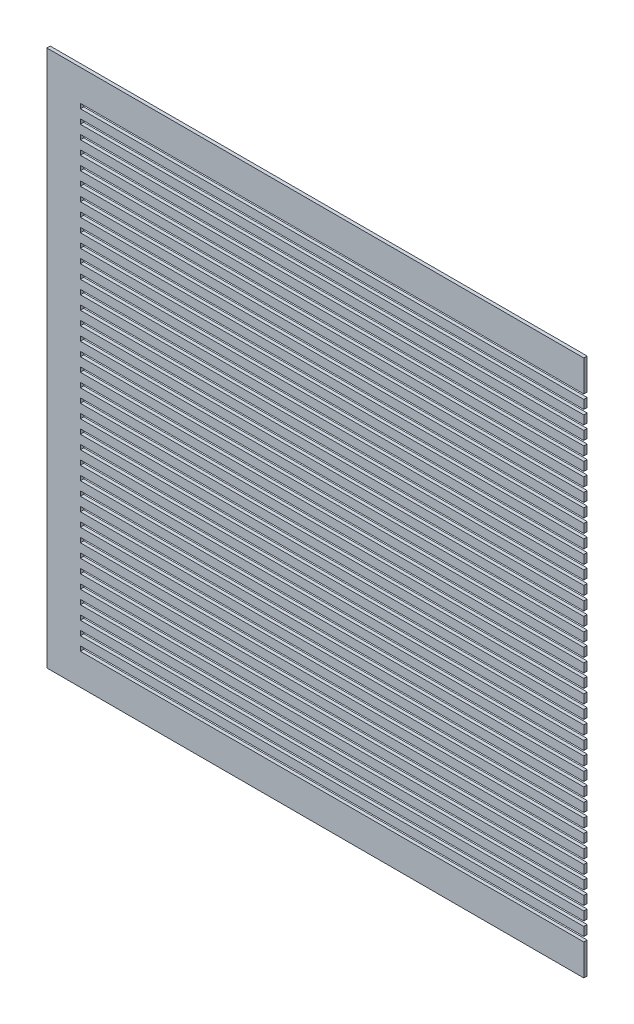
SolidWorks part; units mm, degrees
ref_plane "前视基准面" through (0, 0, 0) normal (0, 0, 1) x (1, 0, 0)
ref_plane "上视基准面" through (0, 0, 0) normal (0, 1, 0) x (1, 0, 0)
ref_plane "右视基准面" through (0, 0, 0) normal (1, 0, 0) x (0, 0, -1)
sketch "草图1" plane through (0, 0, 0) normal (0, 0, 1) x (1, 0, 0)
  line L5 (-75, -66.4634) -> (-75, -65.0634)
  line L6 (-75, -65.0634) -> (75, -65.0634)
  line L7 (-75, -66.4634) -> (75, -66.4634)
  line L8 (-75, -65.0634) -> (75, -65.0634)
  line L9 (-75, -65.7634) -> (75, -65.7634) construction
  line L10 (-75, -62.4634) -> (-75, -61.0634)
  line L11 (-75, -61.0634) -> (75, -61.0634)
  line L13 (-75, -62.4634) -> (75, -62.4634)
  line L14 (-75, -61.0634) -> (75, -61.0634)
  line L15 (-75, -61.7634) -> (75, -61.7634) construction
  line L17 (-75, -58.4634) -> (-75, -57.0634)
  line L18 (75, -70.4634) -> (75, -79.7634)
  line L20 (-75, -57.0634) -> (75, -57.0634)
  line L21 (-75, -58.4634) -> (75, -58.4634)
  line L22 (75, 80.2366) -> (-85, 80.2366)
  line L23 (-85, 80.2366) -> (-85, -79.7634)
  line L25 (-75, -57.0634) -> (75, -57.0634)
  line L26 (-75, -57.7634) -> (75, -57.7634) construction
  line L28 (-75, -54.4634) -> (-75, -53.0634)
  line L29 (-75, -53.0634) -> (75, -53.0634)
  line L30 (-85, -79.7634) -> (75, -79.7634)
  line L31 (-75, -54.4634) -> (75, -54.4634)
  line L33 (-75, -53.0634) -> (75, -53.0634)
  line L34 (-75, -53.7634) -> (75, -53.7634) construction
  line L36 (-75, -50.4634) -> (-75, -49.0634)
  line L37 (-75, -49.0634) -> (75, -49.0634)
  line L38 (-75, -50.4634) -> (75, -50.4634)
  line L39 (-75, -49.0634) -> (75, -49.0634)
  line L41 (-75, -49.7634) -> (75, -49.7634) construction
  line L42 (-75, -46.4634) -> (-75, -45.0634)
  line L44 (-75, -45.0634) -> (75, -45.0634)
  line L45 (-75, -46.4634) -> (75, -46.4634)
  line L46 (-75, -45.0634) -> (75, -45.0634)
  line L47 (-75, -45.7634) -> (75, -45.7634) construction
  line L49 (-75, -42.4634) -> (-75, -41.0634)
  line L50 (-75, -41.0634) -> (75, -41.0634)
  line L52 (-75, -42.4634) -> (75, -42.4634)
  line L53 (-75, -41.0634) -> (75, -41.0634)
  line L54 (-75, -70.4634) -> (-75, -69.0634)
  line L55 (-75, -41.7634) -> (75, -41.7634) construction
  line L57 (-75, -38.4634) -> (-75, -37.0634)
  line L58 (-75, -37.0634) -> (75, -37.0634)
  line L60 (-75, -38.4634) -> (75, -38.4634)
  line L61 (-75, -37.0634) -> (75, -37.0634)
  line L62 (-75, -37.7634) -> (75, -37.7634) construction
  line L63 (-75, -34.4634) -> (-75, -33.0634)
  line L65 (-75, -33.0634) -> (75, -33.0634)
  line L66 (-75, -34.4634) -> (75, -34.4634)
  line L68 (-75, -33.0634) -> (75, -33.0634)
  line L69 (-75, -33.7634) -> (75, -33.7634) construction
  line L70 (-75, -30.4634) -> (-75, -29.0634)
  line L71 (-75, -29.0634) -> (75, -29.0634)
  line L73 (-75, -30.4634) -> (75, -30.4634)
  line L74 (-75, -29.0634) -> (75, -29.0634)
  line L76 (-75, -29.7634) -> (75, -29.7634) construction
  line L77 (-75, -26.4634) -> (-75, -25.0634)
  line L78 (-75, -25.0634) -> (75, -25.0634)
  line L79 (-75, -26.4634) -> (75, -26.4634)
  line L80 (-75, -69.0634) -> (75, -69.0634)
  line L81 (-75, -70.4634) -> (75, -70.4634)
  line L82 (-75, -25.0634) -> (75, -25.0634)
  line L83 (-75, -69.0634) -> (75, -69.0634)
  line L84 (-75, -25.7634) -> (75, -25.7634) construction
  line L85 (-75, -69.7634) -> (75, -69.7634) construction
  line L86 (-75, -22.4634) -> (-75, -21.0634)
  line L87 (-75, -21.0634) -> (75, -21.0634)
  line L88 (-75, -22.4634) -> (75, -22.4634)
  line L89 (-75, -21.0634) -> (75, -21.0634)
  line L90 (-75, -21.7634) -> (75, -21.7634) construction
  line L91 (-75, -18.4634) -> (-75, -17.0634)
  line L92 (-75, -17.0634) -> (75, -17.0634)
  line L93 (-75, -18.4634) -> (75, -18.4634)
  line L94 (-75, -17.0634) -> (75, -17.0634)
  line L95 (-75, -17.7634) -> (75, -17.7634) construction
  line L96 (-75, -14.4634) -> (-75, -13.0634)
  line L97 (-75, -13.0634) -> (75, -13.0634)
  line L98 (-75, -14.4634) -> (75, -14.4634)
  line L99 (-75, -13.0634) -> (75, -13.0634)
  line L100 (-75, -13.7634) -> (75, -13.7634) construction
  line L101 (-75, -10.4634) -> (-75, -9.0634)
  line L102 (-75, -9.0634) -> (75, -9.0634)
  line L103 (-75, -10.4634) -> (75, -10.4634)
  line L104 (-75, -9.0634) -> (75, -9.0634)
  line L105 (-75, -9.7634) -> (75, -9.7634) construction
  line L106 (-75, -6.4634) -> (-75, -5.0634)
  line L107 (-75, -5.0634) -> (75, -5.0634)
  line L108 (-75, -6.4634) -> (75, -6.4634)
  line L109 (-75, -5.0634) -> (75, -5.0634)
  line L110 (-75, -5.7634) -> (75, -5.7634) construction
  line L111 (-75, -2.4634) -> (-75, -1.0634)
  line L112 (-75, -1.0634) -> (75, -1.0634)
  line L113 (-75, -2.4634) -> (75, -2.4634)
  line L114 (-75, -1.0634) -> (75, -1.0634)
  line L115 (-75, -1.7634) -> (75, -1.7634) construction
  line L116 (-75, 1.5366) -> (-75, 2.9366)
  line L117 (-75, 2.9366) -> (75, 2.9366)
  line L118 (-75, 1.5366) -> (75, 1.5366)
  line L119 (-75, 2.9366) -> (75, 2.9366)
  line L120 (-75, 2.2366) -> (75, 2.2366) construction
  line L121 (-75, 5.5366) -> (-75, 6.9366)
  line L122 (-75, 6.9366) -> (75, 6.9366)
  line L123 (-75, 5.5366) -> (75, 5.5366)
  line L124 (-75, 6.9366) -> (75, 6.9366)
  line L125 (-75, 6.2366) -> (75, 6.2366) construction
  line L126 (-75, 9.5366) -> (-75, 10.9366)
  line L127 (-75, 10.9366) -> (75, 10.9366)
  line L128 (-75, 9.5366) -> (75, 9.5366)
  line L129 (-75, 10.9366) -> (75, 10.9366)
  line L130 (-75, 10.2366) -> (75, 10.2366) construction
  line L131 (-75, 13.5366) -> (-75, 14.9366)
  line L132 (-75, 14.9366) -> (75, 14.9366)
  line L133 (-75, 13.5366) -> (75, 13.5366)
  line L134 (-75, 14.9366) -> (75, 14.9366)
  line L135 (-75, 14.2366) -> (75, 14.2366) construction
  line L136 (-75, 17.5366) -> (-75, 18.9366)
  line L137 (-75, 18.9366) -> (75, 18.9366)
  line L138 (-75, 17.5366) -> (75, 17.5366)
  line L139 (-75, 18.9366) -> (75, 18.9366)
  line L140 (-75, 18.2366) -> (75, 18.2366) construction
  line L141 (-75, 21.5366) -> (-75, 22.9366)
  line L142 (-75, 22.9366) -> (75, 22.9366)
  line L143 (-75, 21.5366) -> (75, 21.5366)
  line L144 (-75, 22.9366) -> (75, 22.9366)
  line L145 (-75, 22.2366) -> (75, 22.2366) construction
  line L146 (-75, 25.5366) -> (-75, 26.9366)
  line L147 (-75, 26.9366) -> (75, 26.9366)
  line L148 (-75, 25.5366) -> (75, 25.5366)
  line L149 (-75, 26.9366) -> (75, 26.9366)
  line L150 (-75, 26.2366) -> (75, 26.2366) construction
  line L151 (-75, 29.5366) -> (-75, 30.9366)
  line L152 (-75, 30.9366) -> (75, 30.9366)
  line L153 (-75, 29.5366) -> (75, 29.5366)
  line L154 (-75, 30.9366) -> (75, 30.9366)
  line L155 (-75, 30.2366) -> (75, 30.2366) construction
  line L156 (-75, 33.5366) -> (-75, 34.9366)
  line L157 (-75, 34.9366) -> (75, 34.9366)
  line L158 (-75, 33.5366) -> (75, 33.5366)
  line L159 (-75, 34.9366) -> (75, 34.9366)
  line L160 (-75, 34.2366) -> (75, 34.2366) construction
  line L161 (-75, 37.5366) -> (-75, 38.9366)
  line L162 (-75, 38.9366) -> (75, 38.9366)
  line L163 (-75, 37.5366) -> (75, 37.5366)
  line L164 (-75, 38.9366) -> (75, 38.9366)
  line L165 (-75, 38.2366) -> (75, 38.2366) construction
  line L166 (-75, 41.5366) -> (-75, 42.9366)
  line L167 (-75, 42.9366) -> (75, 42.9366)
  line L168 (-75, 41.5366) -> (75, 41.5366)
  line L169 (-75, 42.9366) -> (75, 42.9366)
  line L170 (-75, 42.2366) -> (75, 42.2366) construction
  line L171 (-75, 45.5366) -> (-75, 46.9366)
  line L172 (-75, 46.9366) -> (75, 46.9366)
  line L173 (-75, 45.5366) -> (75, 45.5366)
  line L174 (-75, 46.9366) -> (75, 46.9366)
  line L175 (-75, 46.2366) -> (75, 46.2366) construction
  line L176 (-75, 49.5366) -> (-75, 50.9366)
  line L177 (-75, 50.9366) -> (75, 50.9366)
  line L178 (-75, 49.5366) -> (75, 49.5366)
  line L179 (-75, 50.9366) -> (75, 50.9366)
  line L180 (-75, 50.2366) -> (75, 50.2366) construction
  line L181 (-75, 53.5366) -> (-75, 54.9366)
  line L182 (-75, 54.9366) -> (75, 54.9366)
  line L183 (-75, 53.5366) -> (75, 53.5366)
  line L184 (-75, 54.9366) -> (75, 54.9366)
  line L185 (-75, 54.2366) -> (75, 54.2366) construction
  line L186 (-75, 57.5366) -> (-75, 58.9366)
  line L187 (-75, 58.9366) -> (75, 58.9366)
  line L188 (-75, 57.5366) -> (75, 57.5366)
  line L189 (-75, 58.9366) -> (75, 58.9366)
  line L190 (-75, 58.2366) -> (75, 58.2366) construction
  line L191 (-75, 61.5366) -> (-75, 62.9366)
  line L192 (-75, 62.9366) -> (75, 62.9366)
  line L193 (-75, 61.5366) -> (75, 61.5366)
  line L194 (-75, 62.9366) -> (75, 62.9366)
  line L195 (-75, 62.2366) -> (75, 62.2366) construction
  line L196 (-75, 65.5366) -> (-75, 66.9366)
  line L197 (-75, 66.9366) -> (75, 66.9366)
  line L198 (-75, 65.5366) -> (75, 65.5366)
  line L199 (-75, 66.9366) -> (75, 66.9366)
  line L200 (-75, 66.2366) -> (75, 66.2366) construction
  line L201 (-75, 69.5366) -> (-75, 70.9366)
  line L202 (-75, 70.9366) -> (75, 70.9366)
  line L203 (-75, 69.5366) -> (75, 69.5366)
  line L204 (-75, 70.9366) -> (75, 70.9366)
  line L205 (-75, 70.2366) -> (75, 70.2366) construction
  line L206 (75, -69.0634) -> (75, -66.4634)
  line L207 (75, -65.0634) -> (75, -62.4634)
  line L208 (75, -61.0634) -> (75, -58.4634)
  line L209 (75, -57.0634) -> (75, -54.4634)
  line L210 (75, -53.0634) -> (75, -50.4634)
  line L211 (75, -49.0634) -> (75, -46.4634)
  line L212 (75, -45.0634) -> (75, -42.4634)
  line L213 (75, -41.0634) -> (75, -38.4634)
  line L214 (75, -37.0634) -> (75, -34.4634)
  line L215 (75, -33.0634) -> (75, -30.4634)
  line L216 (75, -29.0634) -> (75, -26.4634)
  line L217 (75, -25.0634) -> (75, -22.4634)
  line L218 (75, -21.0634) -> (75, -18.4634)
  line L219 (75, -17.0634) -> (75, -14.4634)
  line L220 (75, -13.0634) -> (75, -10.4634)
  line L221 (75, -9.0634) -> (75, -6.4634)
  line L222 (75, -5.0634) -> (75, -2.4634)
  line L223 (75, -1.0634) -> (75, 1.5366)
  line L224 (75, 2.9366) -> (75, 5.5366)
  line L225 (75, 6.9366) -> (75, 9.5366)
  line L226 (75, 10.9366) -> (75, 13.5366)
  line L227 (75, 14.9366) -> (75, 17.5366)
  line L228 (75, 18.9366) -> (75, 21.5366)
  line L229 (75, 22.9366) -> (75, 25.5366)
  line L230 (75, 26.9366) -> (75, 29.5366)
  line L231 (75, 30.9366) -> (75, 33.5366)
  line L232 (75, 34.9366) -> (75, 37.5366)
  line L233 (75, 38.9366) -> (75, 41.5366)
  line L234 (75, 42.9366) -> (75, 45.5366)
  line L235 (75, 46.9366) -> (75, 49.5366)
  line L236 (75, 50.9366) -> (75, 53.5366)
  line L237 (75, 54.9366) -> (75, 57.5366)
  line L238 (75, 58.9366) -> (75, 61.5366)
  line L239 (75, 62.9366) -> (75, 65.5366)
  line L240 (75, 66.9366) -> (75, 69.5366)
  line L241 (75, 70.9366) -> (75, 80.2366)
  line L243 (75, 74.9366) -> (75, 77.5366) [skipped]
  line L244 (75, 70.9366) -> (75, 73.5366) [skipped]
  point P0 (-75, -69.7634)
  dimension "D1" = 160
  dimension "D2" = 1.4
  dimension "D3" = 150
  dimension "D4" = 10
  dimension "D5" = 36
  dimension "D7" = 37
  dimension "D6" = 4
extrude "凸台-拉伸1" add sketch "草图1" along normal blind 1
